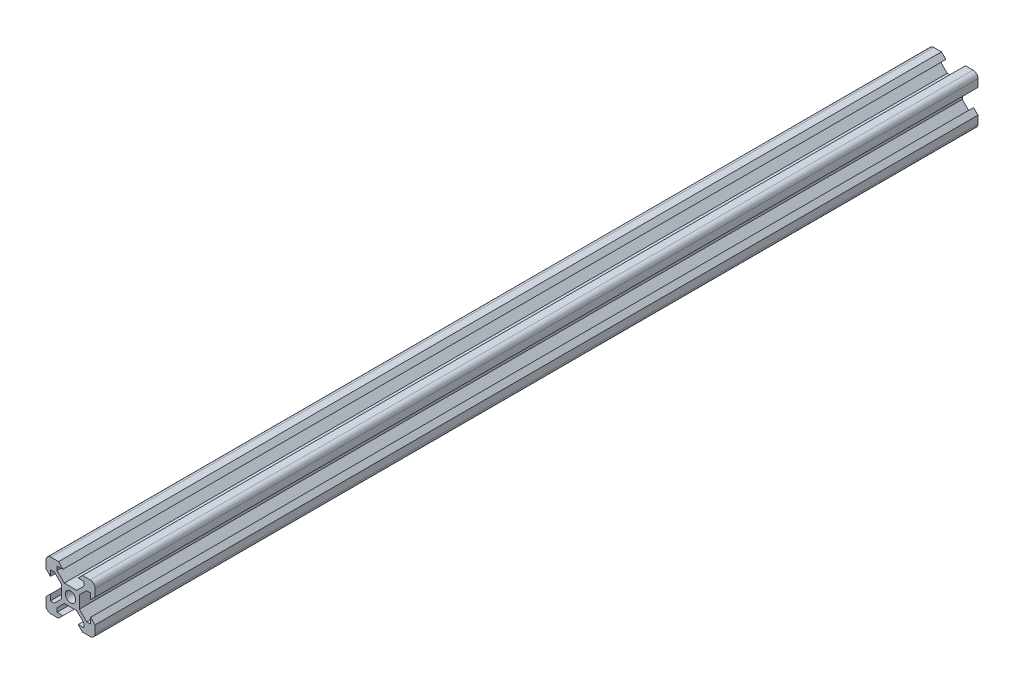
SolidWorks part; units mm, degrees
material "6061 Alloy"
ref_plane "Front Plane" through (0, 0, 0) normal (0, 0, 1) x (1, 0, 0)
ref_plane "Top Plane" through (0, 0, 0) normal (0, 1, 0) x (1, 0, 0)
ref_plane "Right Plane" through (0, 0, 0) normal (1, 0, 0) x (0, 0, -1)
sketch "Sketch1" plane through (0, 0, 0) normal (0, 0, 1) x (1, 0, 0)
  line L0 (-4.9, -10) -> (-5.5, -10)
  line L1 (-10, -10) -> (10, -10) construction
  line L2 (-10, -10) -> (-10, 10) construction
  line L3 (-10, 10) -> (10, 10) construction
  line L4 (10, -10) -> (10, 10) construction
  line L5 (-10, -10) -> (10, 10) construction
  line L6 (-10, 10) -> (10, -10) construction
  line L7 (-3.6, 3.6) -> (3.6, 3.6)
  line L8 (-3.6, 3.6) -> (-3.6, -3.6)
  line L9 (-3.6, -3.6) -> (3.6, -3.6)
  line L10 (3.6, 3.6) -> (3.6, -3.6)
  line L11 (-8, 10) -> (-5.5, 10)
  line L12 (-10, 8) -> (-10, 5.5)
  line L13 (-10, 5.5) -> (-5.5, 5.5)
  line L14 (-5.5, 10) -> (-5.5, 5.5)
  line L15 (8, 10) -> (5.5, 10)
  line L16 (10, 8) -> (10, 5.5)
  line L17 (10, 5.5) -> (5.5, 5.5)
  line L18 (5.5, 10) -> (5.5, 5.5)
  line L19 (8, -10) -> (5.5, -10)
  line L20 (10, -8) -> (10, -5.5)
  line L21 (10, -5.5) -> (5.5, -5.5)
  line L22 (5.5, -10) -> (5.5, -5.5)
  line L23 (-8, -10) -> (-5.5, -10)
  line L24 (-10, -8) -> (-10, -5.5)
  line L25 (-10, -5.5) -> (-5.5, -5.5)
  line L26 (-5.5, -10) -> (-5.5, -5.5)
  line L27 (-3.1, -8.2) -> (-4.9, -10)
  line L28 (-3.1, -8.2) -> (-5.5, -8.2)
  line L29 (4.9, -10) -> (5.5, -10)
  line L30 (3.1, -8.2) -> (4.9, -10)
  line L31 (3.1, -8.2) -> (5.5, -8.2)
  line L32 (-4.9, 10) -> (-5.5, 10)
  line L33 (-3.1, 8.2) -> (-4.9, 10)
  line L34 (-3.1, 8.2) -> (-5.5, 8.2)
  line L35 (4.9, 10) -> (5.5, 10)
  line L36 (0, 0) -> (17.4618, 0) construction
  line L37 (3.1, 8.2) -> (4.9, 10)
  line L38 (3.1, 8.2) -> (5.5, 8.2)
  line L39 (8.2, 3.1) -> (8.2, 5.5)
  line L40 (8.2, 3.1) -> (10, 4.9)
  line L41 (10, 4.9) -> (10, 5.5)
  line L42 (10, -4.9) -> (10, -5.5)
  line L43 (8.2, -3.1) -> (10, -4.9)
  line L44 (8.2, -3.1) -> (8.2, -5.5)
  line L57 (-8.2, -3.1) -> (-10, -4.9)
  line L58 (-10, -4.9) -> (-10, -5.5)
  line L61 (-8.2, -3.1) -> (-8.2, -5.5)
  line L62 (-8.2, 3.1) -> (-10, 4.9)
  line L63 (-10, 4.9) -> (-10, 5.5)
  line L66 (-8.2, 3.1) -> (-8.2, 5.5)
  line L67 (-2.7729, 2.7729) -> (-6.4508, 6.4508) construction
  line L68 (-2.2426, 3.3033) -> (-5.9205, 6.9812)
  line L69 (-3.3033, 2.2426) -> (-6.9812, 5.9205)
  line L70 (6.7372, 6.7372) -> (2.7729, 2.7729)
  line L71 (6.309, -6.309) -> (2.7729, -2.7729)
  line L72 (-2.8687, -2.8687) -> (-6.5971, -6.5971)
  line L73 (6.2069, 7.2675) -> (2.2426, 3.3033)
  line L74 (6.8393, -5.7786) -> (3.3033, -2.2426)
  line L75 (-3.399, -2.3384) -> (-7.1274, -6.0667)
  line L76 (7.2675, 6.2069) -> (3.3033, 2.2426)
  line L77 (5.7786, -6.8393) -> (2.2426, -3.3033)
  line L78 (-2.3384, -3.399) -> (-6.0667, -7.1274)
  circle A0 centre (0, 0) radius 2.1
  arc A1 (-8, -10) -> (-10, -8) centre (-8, -8) cw
  arc A2 (8, -10) -> (10, -8) centre (8, -8) ccw
  arc A3 (8, 10) -> (10, 8) centre (8, 8) cw
  arc A4 (-8, 10) -> (-10, 8) centre (-8, 8) ccw
  point P0 (0, 0)
  dimension "D3" = 4.2
  dimension "D12" = 2
  dimension "D1" = 20
  dimension "D4" = 6.4
  dimension "D5" = 6.4
  dimension "D6" = 6.4
  dimension "D7" = 6.4
  dimension "D8" = 4.5
  dimension "D9" = 4.5
  dimension "D10" = 4.5
  dimension "D11" = 4.5
  dimension "D13" = 45
  dimension "D19" = 45
  dimension "D20" = 6.2
  dimension "D23" = 1.8
  dimension "D24" = 1.8
  dimension "D28" = 0.75
  dimension "D26" = 0.75
  dimension "D27" = 0.75
  dimension "D29" = 0.75
extrude "Boss-Extrude1" add sketch "Sketch1" along normal blind 360
